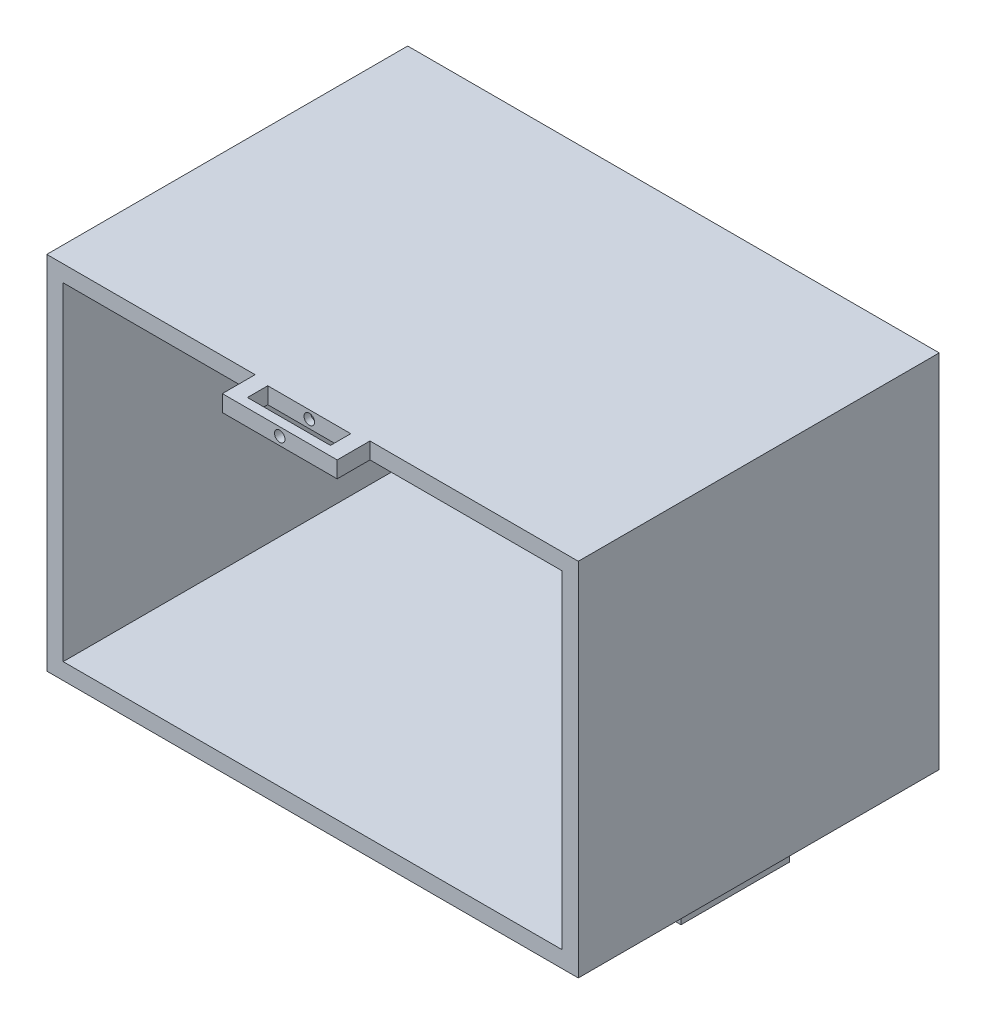
SolidWorks part; units mm, degrees
ref_plane "Front Plane" through (0, 0, 0) normal (0, 0, 1) x (1, 0, 0)
ref_plane "Top Plane" through (0, 0, 0) normal (0, 1, 0) x (1, 0, 0)
ref_plane "Right Plane" through (0, 0, 0) normal (1, 0, 0) x (0, 0, -1)
sketch "Sketch1" plane through (0, 0, 0) normal (0, 0, 1) x (1, 0, 0)
  line L1 (-81, 55) -> (81, 55)
  line L2 (-81, 55) -> (-81, -55)
  line L3 (-81, -55) -> (81, -55)
  line L4 (81, 55) -> (81, -55)
  line L5 (-81, 55) -> (81, -55) construction
  line L6 (-81, -55) -> (81, 55) construction
  point P0 (0, 0)
  dimension "D1" = 110
  dimension "D2" = 162
extrude "Boss-Extrude1" add sketch "Sketch1" along normal mid plane 110
shell "Shell1" thickness 5
sketch "Sketch5" plane through (0, 0, 0) normal (0, 0, 1) x (1, 0, 0)
  line L4 (-67.3, -55) -> (-67.3, -60.3)
  line L6 (-72.3, -55) -> (-72.3, -65.3)
  line L7 (-55.3, -65.3) -> (-72.3, -65.3)
  line L8 (-72.3, -55) -> (-67.3, -55)
  line L9 (-55.3, -65.3) -> (-55.3, -60.3)
  line L11 (-55.3, -60.3) -> (-67.3, -60.3) construction
  line L12 (-67.3, -60.3) -> (-55.3, -60.3)
  line L13 (-81, -55) -> (81, -55) construction
  line L14 (-55, -55) -> (-55, -172) construction
  line L15 (0, 0) -> (0, -21.3223) construction
  line L16 (67.3, -55) -> (67.3, -60.3)
  line L17 (72.3, -55) -> (67.3, -55)
  line L18 (72.3, -55) -> (72.3, -65.3)
  line L19 (55.3, -65.3) -> (72.3, -65.3)
  line L20 (55.3, -65.3) -> (55.3, -60.3)
  line L21 (67.3, -60.3) -> (55.3, -60.3)
  dimension "D2" = 5.3
  dimension "D3" = 12.3
  dimension "D4" = 0.3
  dimension "D1" = 5
extrude "Boss-Extrude3" add sketch "Sketch5" along normal mid plane 30
sketch "Sketch6" plane through (0, 0, -15) normal (0, 0, -1) x (-1, 0, 0)
  line L0 (81, -55) -> (-81, -55) construction
  line L1 (72.3, -65.3) -> (55.3, -65.3)
  line L2 (72.3, -65.3) -> (72.3, -55)
  line L3 (72.3, -55) -> (55.3, -55)
  line L4 (55.3, -65.3) -> (55.3, -55)
  line L6 (0, 0) -> (0, -13.2857) construction
  line L7 (-72.3, -55) -> (-55.3, -55)
  line L8 (-55.3, -65.3) -> (-55.3, -55)
  line L9 (-72.3, -65.3) -> (-55.3, -65.3)
  line L10 (-72.3, -65.3) -> (-72.3, -55)
extrude "Boss-Extrude4" add sketch "Sketch6" along normal blind 3
sketch "Sketch8" plane through (0, 0, 0) normal (1, 0, 0) x (0, 0, -1)
  line L1 (-55, 55) -> (-65, 55)
  line L2 (-55, 55) -> (-55, 50)
  line L3 (-55, 50) -> (-65, 50)
  line L4 (-65, 55) -> (-65, 50)
  dimension "D1" = 5
  dimension "D2" = 10
extrude "Boss-Extrude5" add sketch "Sketch8" along normal mid plane 35
sketch "Sketch9" plane through (0, 55, 0) normal (0, 1, 0) x (1, 0, 0)
  line L0 (0, 0) -> (0, -65) construction
  line L1 (17.5, -65) -> (-17.5, -65) construction
  line L2 (-17.5, -55) -> (-81, -55) construction
  line L3 (-12.65, -62.2) -> (12.65, -62.2)
  line L4 (-12.65, -62.2) -> (-12.65, -56)
  line L5 (-12.65, -56) -> (12.65, -56)
  line L6 (12.65, -62.2) -> (12.65, -56)
  line L7 (-12.65, -62.2) -> (12.65, -56) construction
  line L8 (-12.65, -56) -> (12.65, -62.2) construction
  point P5 (0, -59.1)
  dimension "D1" = 1
  dimension "D2" = 25.3
  dimension "D3" = 6.2
extrude "Cut-Extrude1" cut sketch "Sketch9" against normal blind 5
sketch "Sketch10" plane through (0, 0, 65) normal (0, 0, 1) x (1, 0, 0)
  line L0 (-17.5, 55) -> (17.5, 50) construction
  circle A0 centre (0, 52.5) radius 1.6
  dimension "D1" = 3.2
extrude "Cut-Extrude2" cut sketch "Sketch10" against normal blind 11
